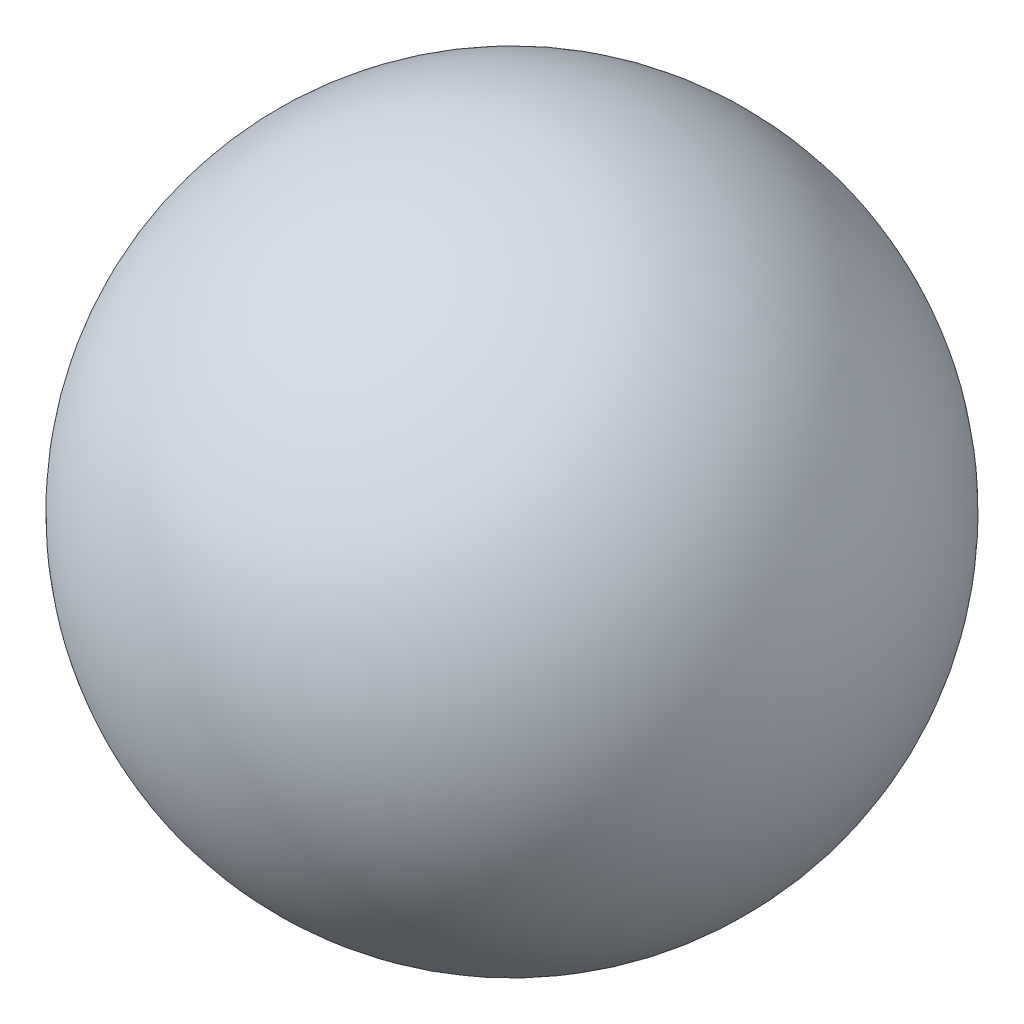
SolidWorks part; units mm, degrees
ref_plane "Front Plane" through (0, 0, 0) normal (0, 0, 1) x (1, 0, 0)
ref_plane "Top Plane" through (0, 0, 0) normal (0, 1, 0) x (1, 0, 0)
ref_plane "Right Plane" through (0, 0, 0) normal (1, 0, 0) x (0, 0, -1)
sketch "Sketch3" plane through (0, 0, 0) normal (0, 0, 1) x (1, 0, 0)
  line L0 (3.929, 2.8546) -> (-1.5007, 4.6188) construction
  line L1 (-1.5007, 4.6188) -> (-4.8565, 0) construction
  line L2 (-4.8565, 0) -> (-1.5007, -4.6188) construction
  line L3 (-1.5007, -4.6188) -> (3.929, -2.8546) construction
  line L4 (3.929, -2.8546) -> (3.929, 2.8546) construction
  line L5 (-1.5007, 4.6188) -> (0, 0) construction
  line L6 (0, 0) -> (-4.8565, 0) construction
  line L7 (-1.5007, -4.6188) -> (0, 0) construction
  line L8 (0, 0) -> (3.929, -2.8546) construction
  line L9 (0, 0) -> (3.929, 2.8546) construction
  circle A0 centre (0, 0) radius 4.8565
sketch "Sketch1" plane through (0, 0, 0) normal (0, 1, 0) x (1, 0, 0)
  line L0 (0, 4.8565) -> (0, -4.8565)
  line L1 (0, 0) -> (4.8565, 0) construction
  arc A0 (0, -4.8565) -> (0, 4.8565) centre (0, 0) ccw
  dimension "D1" = 9.713
revolve "Revolve3" add sketch "Sketch1" angle 360 about L0
sketch "Sketch2" plane through (0, 0, 0) normal (0, 1, 0) x (1, 0, 0)
  line L0 (0, 0) -> (0, 4.8565)
  line L1 (0, 0) -> (4.8565, 0) construction
  line L2 (0, 0) -> (0, -4.8565) construction
  arc A0 (0, -4.8565) -> (0, 4.8565) centre (0, 0) ccw construction
